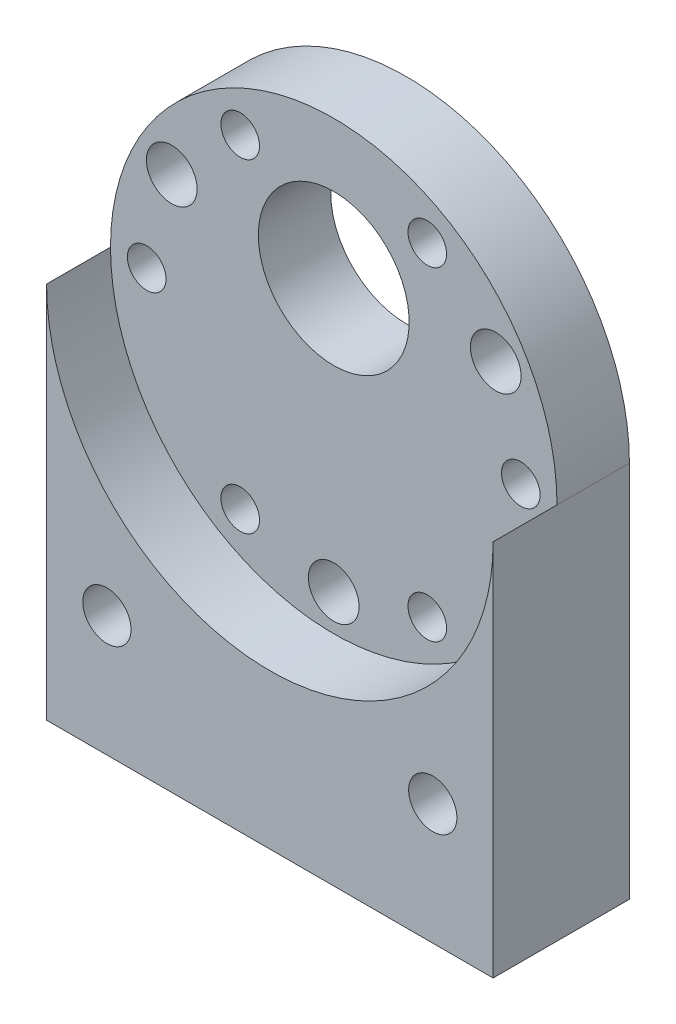
SolidWorks part; units mm, degrees
material "ABS"
ref_plane "Front Plane" through (0, 0, 0) normal (0, 0, 1) x (1, 0, 0)
ref_plane "Top Plane" through (0, 0, 0) normal (0, 1, 0) x (1, 0, 0)
ref_plane "Right Plane" through (0, 0, 0) normal (1, 0, 0) x (0, 0, -1)
sketch "Sketch1" plane through (0, 0, 0) normal (0, 0, 1) x (1, 0, 0)
  circle A0 centre (0, 7) radius 6.25
  circle A1 centre (0, 7) radius 6.25 construction
  circle A2 centre (15.5, 0) radius 1.6
  circle A3 centre (0, 0) radius 18.5
  circle A4 centre (7.75, -13.4234) radius 1.6
  circle A5 centre (-7.75, -13.4234) radius 1.6
  circle A6 centre (-15.5, 0) radius 1.6
  circle A7 centre (-7.75, 13.4234) radius 1.6
  circle A8 centre (7.75, 13.4234) radius 1.6
  circle A9 centre (13.4234, 7.75) radius 2.1
  circle A10 centre (0, -15.5) radius 2.1
  circle A11 centre (-13.4234, 7.75) radius 2.1
  point P22 (0, 0)
  point P31 (0, 0)
  dimension "D1" = 3.2
  dimension "D3" = 37
  dimension "D4" = 3
  dimension "D5" = 4.2
  dimension "D6" = 15.5
  dimension "D2" = 6
extrude "Boss-Extrude1" add sketch "Sketch1" along normal up to surface (6 mm away)
sketch "Sketch3" plane through (0, 0, 6) normal (0, 0, 1) x (1, 0, 0)
  line L0 (-110, -6.301) -> (40, -6.301) construction
  line L1 (-18.5, 0) -> (18.5, 0) construction
  line L2 (-18.5, 0) -> (-18.5, -31.301)
  line L3 (-18.5, -31.301) -> (18.5, -31.301)
  line L4 (18.5, 0) -> (18.5, -31.301)
  line L5 (-18.5, 0) -> (18.5, -31.301) construction
  line L6 (-18.5, -31.301) -> (18.5, 0) construction
  line L7 (0, -31.301) -> (0, 0) construction
  circle A0 centre (0, 0) radius 18.5
  circle A1 centre (-13.5, -21.301) radius 2
  circle A2 centre (13.5, -21.301) radius 2
  point P7 (0, -15.6505)
  circle M16 centre (0, 0) radius 18.5
  dimension "D4" = 4
  dimension "D6" = 10
  dimension "D1" = 25
  dimension "D2" = 37
  dimension "D3" = 18.5
  dimension "D5" = 5
extrude "Boss-Extrude2" add sketch "Sketch3" along normal up to surface and the other way up to surface contours L4 L2 L3 A1 A2 M16
sketch "Sketch4" plane through (0, 0, 0) normal (0, 0, -1) x (-1, 0, 0)
  circle A0 centre (-13.5, -21.301) radius 3.5
  circle A1 centre (13.5, -21.301) radius 3.5
  dimension "D1" = 7
  dimension "D2" = 7
extrude "Cut-Extrude1" cut sketch "Sketch4" against normal blind 5
